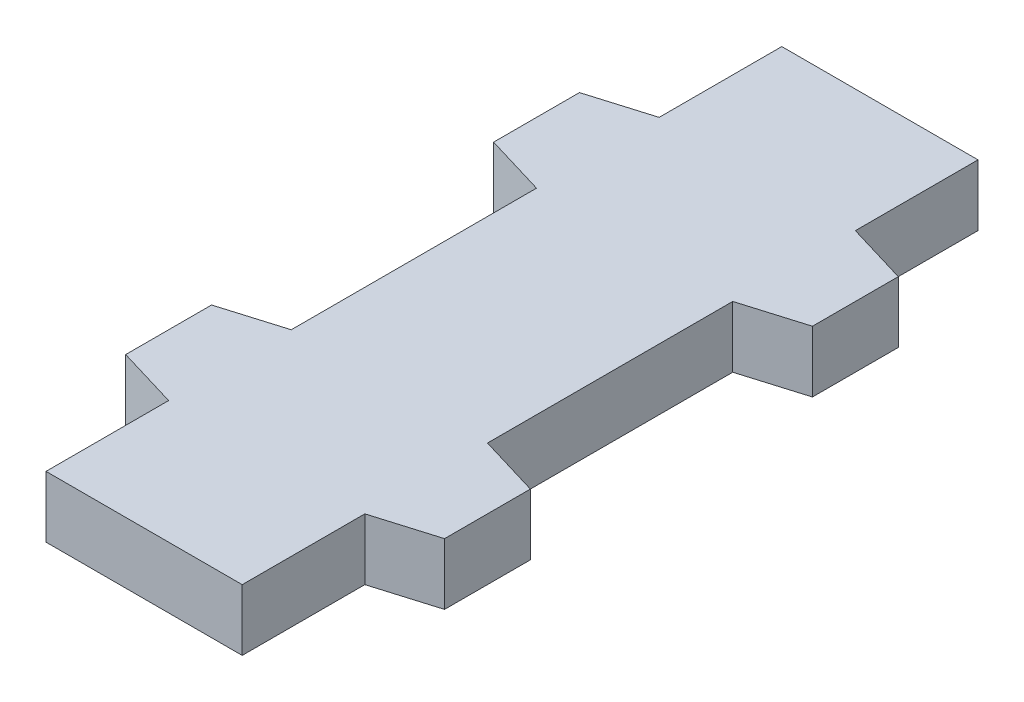
SolidWorks part; units mm, degrees
ref_plane "Front Plane" through (0, 0, 0) normal (0, 0, 1) x (1, 0, 0)
ref_plane "Top Plane" through (0, 0, 0) normal (0, 1, 0) x (1, 0, 0)
ref_plane "Right Plane" through (0, 0, 0) normal (1, 0, 0) x (0, 0, -1)
sketch "Sketch1" plane through (0, 0, 0) normal (0, 1, 0) x (1, 0, 0)
  line L0 (0, 0) -> (0, 30) construction
  line L1 (-8, -30) -> (8, -30)
  line L2 (-8, -30) -> (-8, -20)
  line L3 (-8, 30) -> (8, 30)
  line L4 (8, -30) -> (8, -20)
  line L5 (-8, -30) -> (8, 30) construction
  line L6 (-8, 30) -> (8, -30) construction
  line L7 (0, 0) -> (-8, 0) construction
  line L8 (-8, 20) -> (-13, 18.5)
  line L9 (-13, 18.5) -> (-13, 11.5)
  line L10 (-13, 11.5) -> (-8, 10)
  line L11 (13, 11.5) -> (8, 10)
  line L12 (13, 18.5) -> (13, 11.5)
  line L13 (8, 20) -> (13, 18.5)
  line L14 (-8, -20) -> (-13, -18.5)
  line L15 (-13, -18.5) -> (-13, -11.5)
  line L16 (-13, -11.5) -> (-8, -10)
  line L17 (13, -11.5) -> (8, -10)
  line L18 (13, -18.5) -> (13, -11.5)
  line L19 (8, -20) -> (13, -18.5)
  line L20 (-8, 20) -> (-8, 30)
  line L21 (8, 20) -> (8, 30)
  line L22 (-8, -10) -> (-8, 10)
  line L23 (8, -10) -> (8, 10)
  point P0 (0, 0)
  point P12 (0, 0)
  point P14 (-13.7326, 14.1092)
  point P15 (-13, 15)
  point P16 (0, 15)
  dimension "D1" = 60
  dimension "D2" = 16
  dimension "D3" = 7
  dimension "D4" = 10
  dimension "D5" = 5
extrude "Boss-Extrude1" add sketch "Sketch1" along normal mid plane 5
